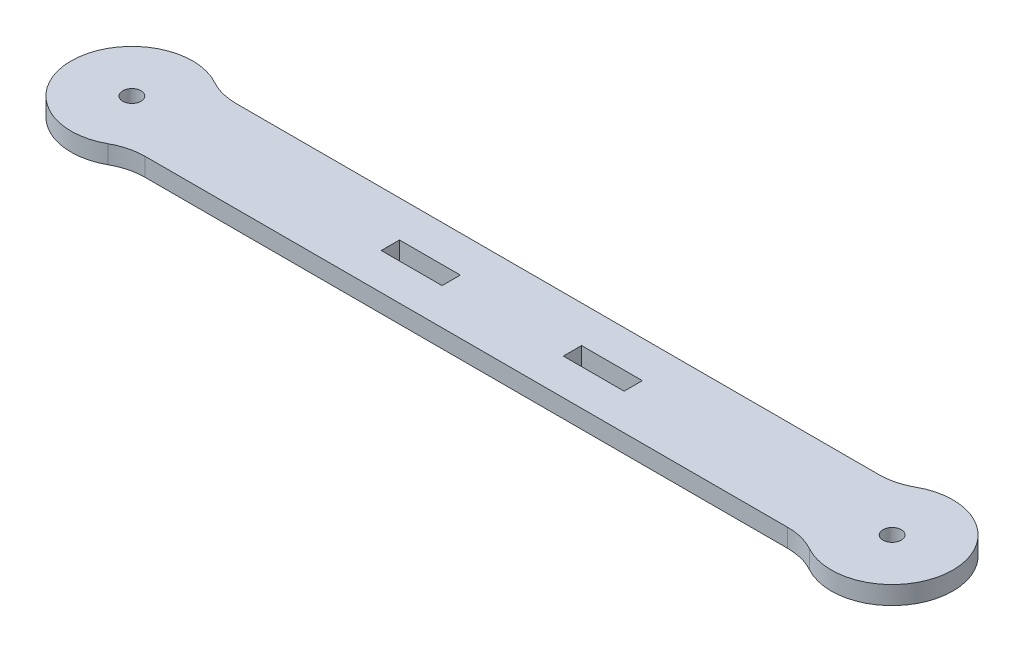
SolidWorks part; units mm, degrees
ref_plane "前视基准面" through (0, 0, 0) normal (0, 0, 1) x (1, 0, 0)
ref_plane "上视基准面" through (0, 0, 0) normal (0, 1, 0) x (1, 0, 0)
ref_plane "右视基准面" through (0, 0, 0) normal (1, 0, 0) x (0, 0, -1)
sketch "草图1" plane through (0, 0, 0) normal (0, 1, 0) x (1, 0, 0)
  line L0 (-120.37, 0) -> (120.37, 0) construction
  line L1 (0, 79.1414) -> (0, -79.1414) construction
  line L2 (-55.8856, -7.5) -> (55.8856, -7.5)
  line L3 (-55.8856, 7.5) -> (55.8856, 7.5)
  line L5 (-20, 1.5) -> (-10, 1.5)
  line L6 (-20, 1.5) -> (-20, -1.5)
  line L7 (-20, -1.5) -> (-10, -1.5)
  line L8 (-10, 1.5) -> (-10, -1.5)
  line L9 (10, 1.4359) -> (20, 1.4359)
  line L10 (10, 1.4359) -> (10, -1.5641)
  line L11 (10, -1.5641) -> (20, -1.5641)
  line L12 (20, 1.4359) -> (20, -1.5641)
  arc A0 (-55.8856, 7.5) -> (-55.8856, -7.5) centre (-62.5, 0) ccw
  arc A1 (55.8856, -7.5) -> (55.8856, 7.5) centre (62.5, 0) ccw
  circle A2 centre (-62.5, 0) radius 1.5
  circle A3 centre (62.5, 0) radius 1.5
  point P4 (0, 0)
  point P8 (0, 0)
  dimension "D1" = 10
  dimension "D3" = 3
  dimension "D2" = 15
  dimension "D4" = 10
  dimension "D5" = 3
  dimension "D6" = 20
  dimension "D7" = 10
  dimension "D8" = 125
extrude "凸台-拉伸1" add sketch "草图1" along normal blind 3
fillet "圆角1" radius 10 4 edges at (55.8856, 1.5, 7.5) (-55.8856, 1.5, 7.5) (55.8856, 1.5, -7.5) (-55.8856, 1.5, -7.5)
